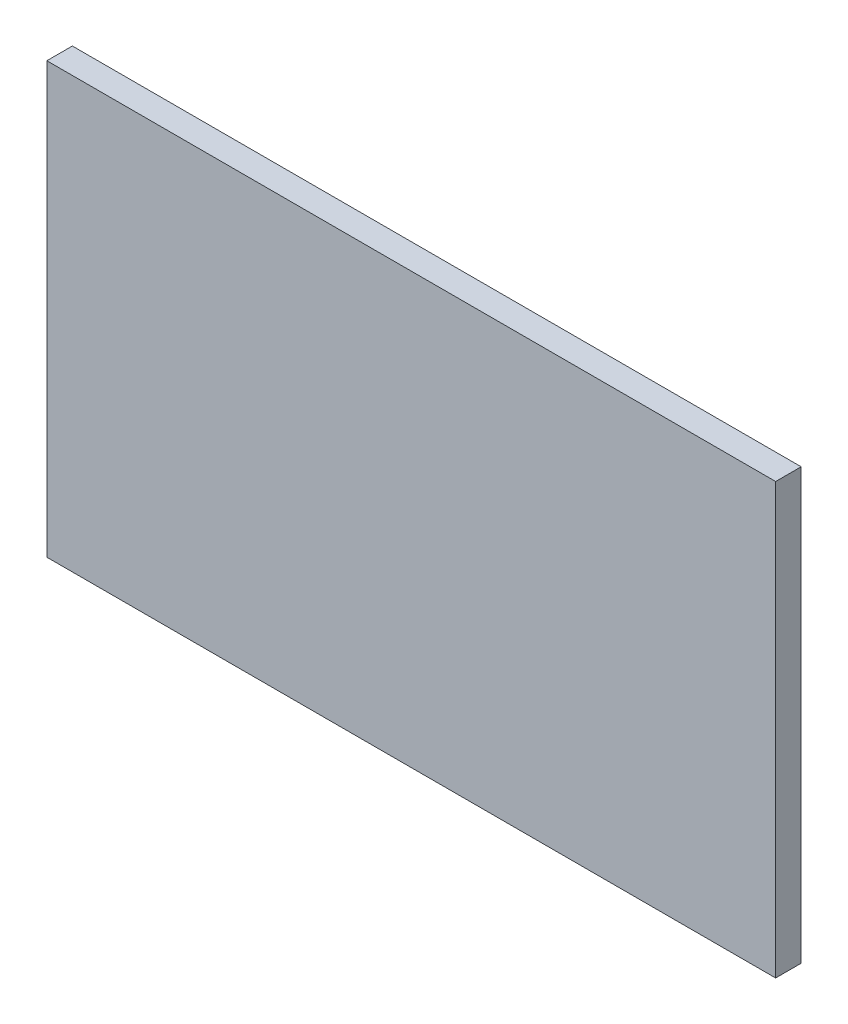
SolidWorks part; units mm, degrees
ref_plane "Front Plane" through (0, 0, 0) normal (0, 0, 1) x (1, 0, 0)
ref_plane "Top Plane" through (0, 0, 0) normal (0, 1, 0) x (1, 0, 0)
ref_plane "Right Plane" through (0, 0, 0) normal (1, 0, 0) x (0, 0, -1)
sketch "Sketch1" plane through (0, 0, 0) normal (0, 0, 1) x (1, 0, 0)
  line L1 (-254, 149.86) -> (254, 149.86)
  line L2 (-254, 149.86) -> (-254, -149.86)
  line L3 (-254, -149.86) -> (254, -149.86)
  line L4 (254, 149.86) -> (254, -149.86)
  line L5 (-254, 149.86) -> (254, -149.86) construction
  line L6 (-254, -149.86) -> (254, 149.86) construction
  point P0 (0, 0)
  dimension "D1" = 508
  dimension "D2" = 299.72
extrude "Boss-Extrude1" add sketch "Sketch1" along normal blind 17.78
